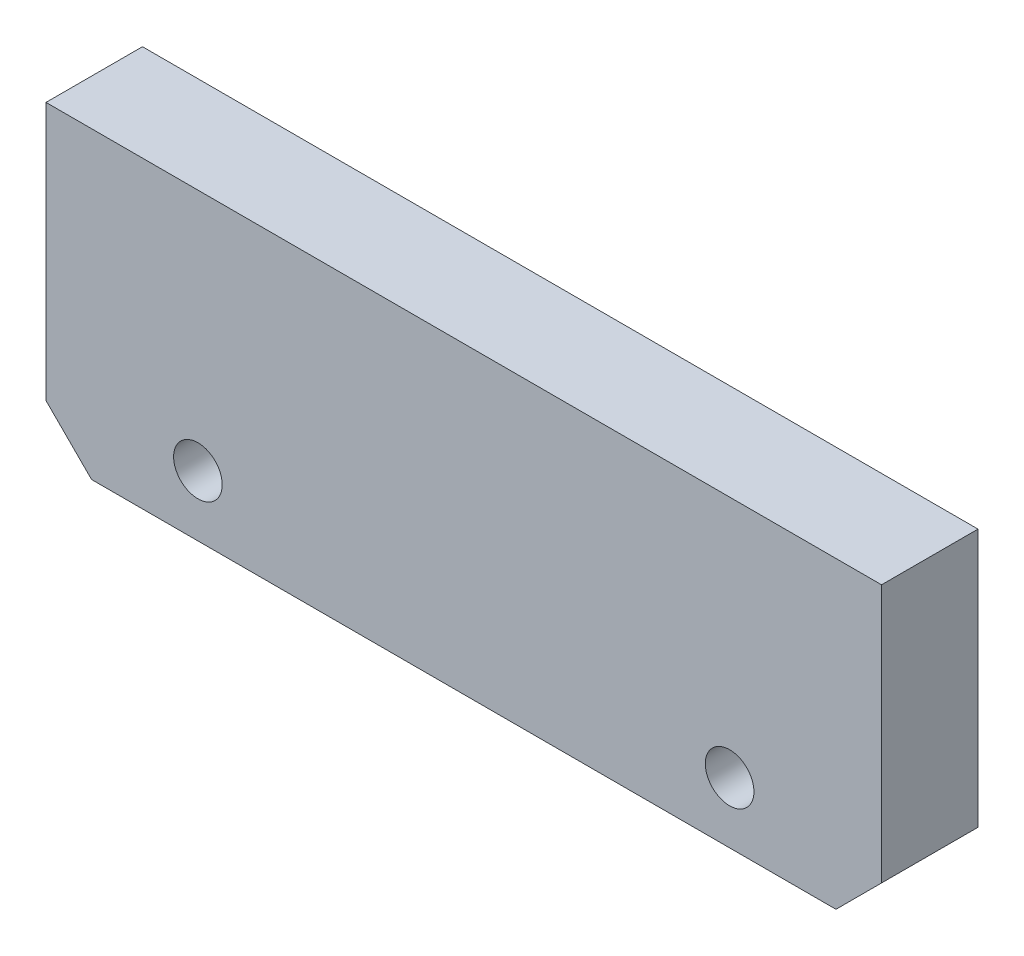
SolidWorks part; units mm, degrees
ref_plane "Front Plane" through (0, 0, 0) normal (0, 0, 1) x (1, 0, 0)
ref_plane "Top Plane" through (0, 0, 0) normal (0, 1, 0) x (1, 0, 0)
ref_plane "Right Plane" through (0, 0, 0) normal (1, 0, 0) x (0, 0, -1)
sketch "Sketch1" plane through (0, 0, 0) normal (0, 0, 1) x (1, 0, 0)
  line L0 (0, 0) -> (55, 0)
  line L5 (55, 0) -> (55, -20)
  line L6 (55, -20) -> (0, -20)
  line L7 (0, -20) -> (0, 0)
  dimension "D1" = 55
  dimension "D2" = 20
extrude "Boss-Extrude1" add sketch "Sketch1" along normal blind 6.35
hole_wizard "Ø3.0mm Dowel Hole1" positions "Sketch2" profile "Sketch3" hole size "Ø3.0" standard "AS" end condition through all
sketch "Sketch2" plane through (0, 0, 6.35) normal (0, 0, 1) x (1, 0, 0)
  line L3 (55, 0) -> (0, 0) construction
  point P0 (10, -16)
  point P16 (45, -16)
  dimension "D1" = 10
  dimension "D2" = 16
  dimension "D3" = 10
sketch "Sketch3" plane through (10, -16, 6.35) normal (1, 0, 0) x (0, -1, 0)
  line L0 (0, 0) -> (0, 6.35)
  line L1 (0, 6.35) -> (1.6, 6.35)
  line L2 (1.6, 6.35) -> (1.6, 0)
  line L5 (1.6, 0) -> (0, 0)
  line L11 (0, -6.35) -> (0, 107.95) construction
  dimension "Thru Hole Dia." = 3.2
  dimension "Thru Hole Depth" = 6.35
chamfer "Chamfer1" distance 3 angle 45 2 edges at (55, -20, 3.175) (0, -20, 3.175)
sketch "Sketch4" plane through (0, 0, 6.35) normal (0, 0, 1) x (1, 0, 0)
  point P0 (10, -16)
  point P1 (45, -16)
sketch "Sketch5" plane through (0, 0, 0) normal (0, 0, -1) x (-1, 0, 0)
  point P0 (-45, -16)
  point P1 (-10, -16)
equation "\"D3@Sketch2\"=\"D1@Sketch2\""
